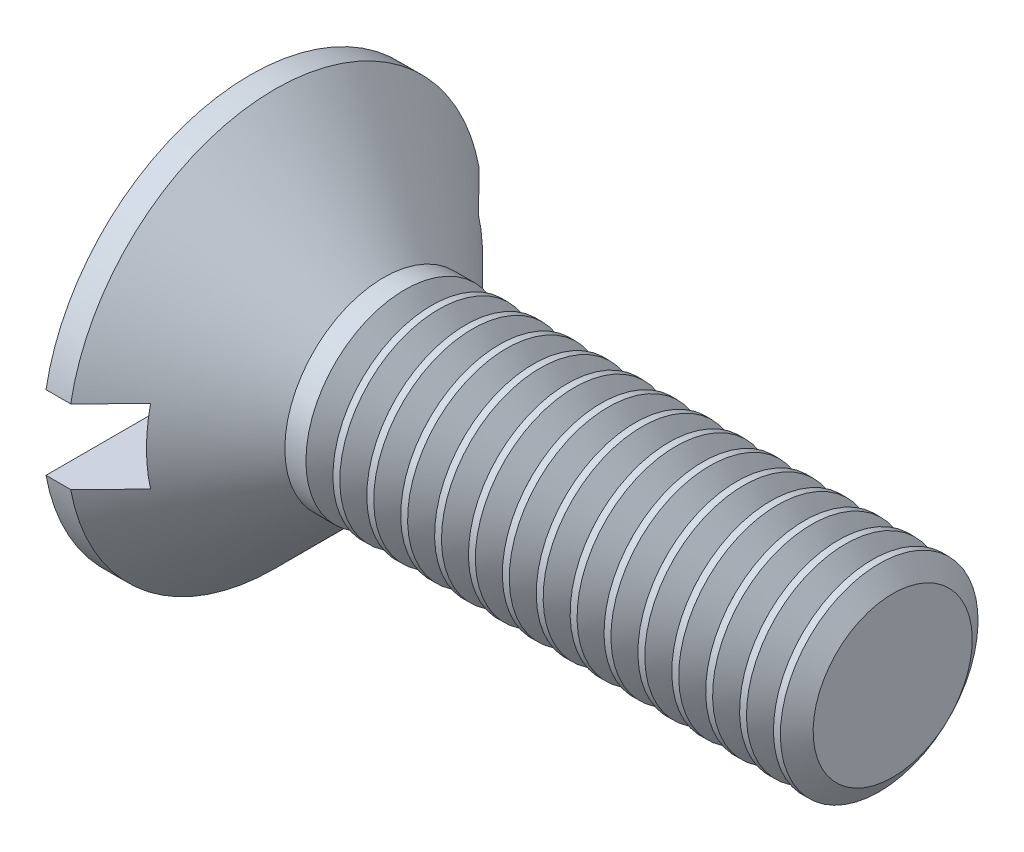
SolidWorks part; units mm, degrees
revolve "Base-Revolve" add sketch "BodySke" angle 360 about L5
sketch "BodySke" plane through (0, 0, 0) normal (0, 0, 1) x (1, 0, 0)
  line L0 (0, 0) -> (0, 4.2)
  line L1 (0, 4.2) -> (0.5, 4.2)
  line L2 (2.7, 2) -> (13, 2)
  line L3 (13, 2) -> (13, 0)
  line L4 (13, 0) -> (0, 0)
  line L5 (-6.35, 0) -> (82.55, 0) construction
  line L6 (2.7, -2) -> (13, -2) construction
  line L7 (0.5, -4.2) -> (2.7, -2) construction
  line L8 (0.5, 4.2) -> (2.7, 2)
  line L9 (0, -4.2) -> (0.5, -4.2) construction
  line L10 (3.4, 3.5875) -> (3.4, -5.9375) construction
  line L11 (0, 6.35) -> (0, -3.175) construction
  dimension "Diameter" = 4
  dimension "Length" = 13
  dimension "Head_ht" = 2.7
  dimension "Head_dia" = 8.4
  dimension "Head_ang" = 90
  dimension "D6" = 0.5
  dimension "Advance" = 0.7
  dimension "Thread_nom" = 13
cosmetic thread "ThreadCosmetic" [suppressed] parameters "Thread_length"=9.6, "Thread_minor"=3.22
extrude "Slot" cut sketch "Sketch2" against normal blind 1.3
sketch "Sketch2" plane through (0, 0, 0) normal (-1, 0, 0) x (0, 0, 1)
  line L0 (-4.2, -0.75) -> (4.2, -0.75)
  line L1 (-4.2, -0.75) -> (-4.2, 0.75)
  line L2 (4.2, 0.75) -> (-4.2, 0.75)
  line L3 (4.2, 0.75) -> (4.2, -0.75)
  dimension "Slot_width" = 1.5
  dimension "D1" = 0.75
  dimension "D2" = 8.4
  dimension "D3" = 4.2
ref_plane "Plane1" through (0, 0, 0) normal (0, 0, 1) x (1, 0, 0)
ref_plane "Plane2" through (0, 0, 0) normal (0, 1, 0) x (1, 0, 0)
ref_plane "Plane3" through (0, 0, 0) normal (1, 0, 0) x (0, 0, -1)
sketch "Sketch3" plane through (0, 0, 0) normal (-1, 0, 0) x (0, 0, 1)
  line L0 (-0.48, 2.23) -> (0.48, 2.23)
  line L1 (0.48, 2.23) -> (0.48, -2.23)
  line L2 (0.48, -2.23) -> (-0.48, -2.23)
  line L3 (-0.48, -2.23) -> (-0.48, 2.23)
  dimension "Cross_dia" = 4.46
  dimension "Cross_width" = 0.96
  dimension "D1" = 2.23
  dimension "D2" = 0.48
ref_plane "Plane4" through (2.65, 0, 0) normal (-1, 0, 0) x (0, 0, 1)
sketch "Sketch4" plane through (2.65, 0, 0) normal (-1, 0, 0) x (0, 0, 1)
  line L0 (-0.24, 0.24) -> (0.24, 0.24)
  line L3 (0.24, 0.24) -> (0.24, -0.24)
  line L4 (0.24, -0.24) -> (-0.24, -0.24)
  line L5 (-0.24, -0.24) -> (-0.24, 0.24)
  dimension "D2" = 0.48
  dimension "D1" = 0.48
  dimension "D3" = 0.24
  dimension "D4" = 0.24
loft "Cross" [suppressed] cut profiles "Sketch3", "Sketch4"
pattern_circular "CirPattern1" [suppressed] count 2 every 90 about axis through (-6.35, 0, 0) along (1, 0, 0)
sketch "ThdSchSke" plane through (0, 0, 0) normal (0, 0, 1) x (1, 0, 0)
  line L0 (3.4, -1.61) -> (3.1269, -2)
  line L1 (3.4, -1.61) -> (3.6731, -2)
  line L2 (3.6731, -2) -> (3.6731, -2.5)
  line L3 (-3.175, 0) -> (5.1513, 0) construction
  line L5 (3.6731, -2.5) -> (3.1269, -2.5)
  line L6 (3.1269, -2.5) -> (3.1269, -2)
  line L7 (0, 4.2) -> (0, 0.75) construction
  dimension "Diameter" = 4
  dimension "Thread_minor" = 3.22
  dimension "Start" = 3.4
revolve "ThreadSchematic" cut sketch "ThdSchSke" angle 360 about L3
pattern_linear "ThdSchPat" count 15 spacing 0.6857 along (1, 0, 0) of "ThreadSchematic"
equation "\"D1@Sketch3\" = \"Cross_dia@Sketch3\" / 2"
equation "\"D2@Sketch3\" = \"Cross_width@Sketch3\" / 2"
equation "\"D1@Sketch4\" = \"Cross_width@Sketch3\" *.5"
equation "\"D2@Sketch4\" = \"D1@Sketch4\""
equation "\"D4@Sketch4\" = \"D2@Sketch4\" / 2"
equation "\"D3@Sketch4\" = \"D1@Sketch4\" / 2"
equation "\"D1@Sketch2\" = \"Slot_width@Sketch2\" / 2"
equation "\"D2@Sketch2\" = \"Head_dia@BodySke\""
equation "\"D3@Sketch2\" = \"D2@Sketch2\" / 2"
equation "\"Thread_length@ThreadCosmetic\" = ((sgn( (\"Length@BodySke\" - \"Advance@BodySke\" - \"Head_ht@BodySke\" ) - \"Thread_nom@BodySke\" )-1)*( (\"Length@BodySke\" - \"Advance@BodySke\" - \"Head_ht@BodySke\" ) - \"Thread_nom@BodySke\" ))/-2+ \"Thread_nom@BodySke\""
equation "\"Thread_minor@ThdSchSke\" = \"Thread_minor@ThreadCosmetic\""
equation "\"Diameter@ThdSchSke\" = \"Diameter@BodySke\""
equation "\"Overcut@ThdSchSke\" = \"Diameter@BodySke\" * 1.25"
equation "\"Start@ThdSchSke\" = 0.000001 + \"Length@BodySke\" - \"Thread_length@ThreadCosmetic\"  '---Countersunk---"
equation "\"Num_threads@ThdSchPat\" = int( \"Thread_length@ThreadCosmetic\" / \"Advance@BodySke\" + 0.999 )  + 1"
equation "\"Advance@ThdSchPat\" = \"Thread_length@ThreadCosmetic\" /  (\"Num_threads@ThdSchPat\" - 1) 'relax it"
